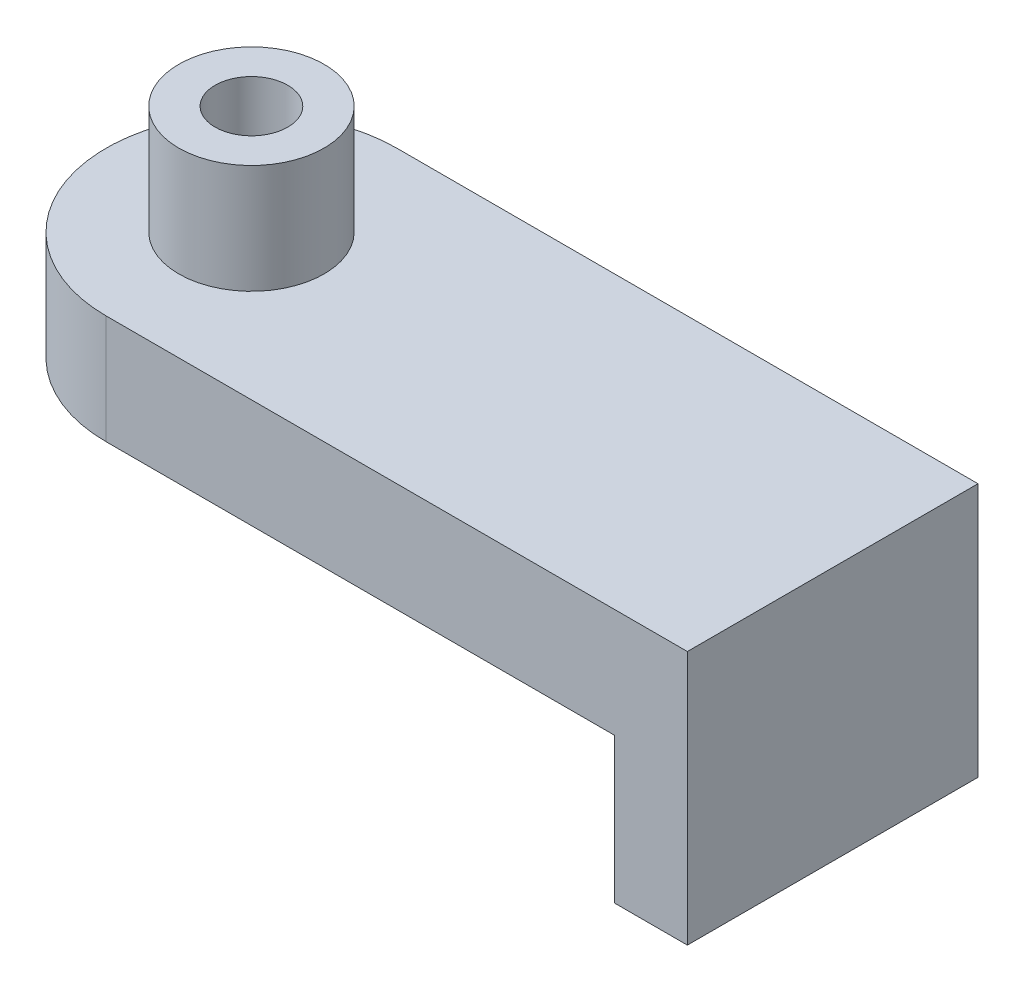
SolidWorks part; units mm, degrees
ref_plane "Alzado" through (0, 0, 0) normal (0, 0, 1) x (1, 0, 0)
ref_plane "Planta" through (0, 0, 0) normal (0, 1, 0) x (1, 0, 0)
ref_plane "Vista lateral" through (0, 0, 0) normal (1, 0, 0) x (0, 0, -1)
sketch "Croquis2" plane through (0, 0, 0) normal (0, 1, 0) x (1, 0, 0)
  line L1 (-40, 20) -> (40, 20)
  line L3 (-40, -20) -> (40, -20)
  line L4 (40, 20) -> (40, -20)
  arc A0 (-40, 20) -> (-40, -20) centre (-40, 0) ccw
  circle A2 centre (-40, 0) radius 5
  point P7 (0, 20)
  dimension "D3" = 20
  dimension "D5" = 10
  dimension "D1" = 80
  dimension "D2" = 40
extrude "Saliente-Extruir1" add sketch "Croquis2" along normal blind 15
sketch "Croquis3" plane through (0, 15, 0) normal (0, 1, 0) x (1, 0, 0)
  circle A0 centre (-40, 0) radius 5 construction
  circle A3 centre (-40, 0) radius 5
  circle A4 centre (-40, 0) radius 10
  dimension "D1" = 20
extrude "Saliente-Extruir2" add sketch "Croquis3" along normal blind 15
sketch "Croquis4" plane through (0, 0, 0) normal (0, -1, 0) x (1, 0, 0)
  line L0 (40, -20) -> (-40, -20) construction
  line L1 (40, 20) -> (30, 20)
  line L2 (40, 20) -> (40, -20)
  line L3 (40, -20) -> (30, -20)
  line L4 (30, 20) -> (30, -20)
  dimension "D1" = 10
extrude "Saliente-Extruir3" add sketch "Croquis4" along normal blind 20
